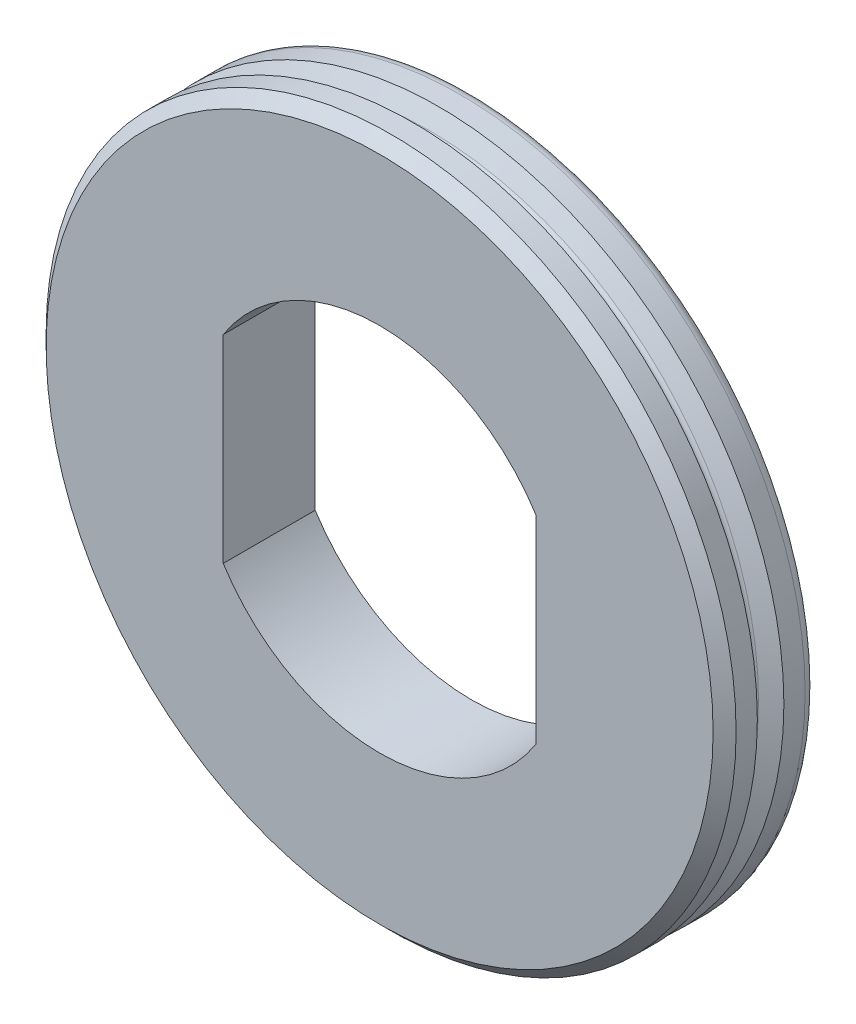
SolidWorks part; units mm, degrees
material "AISI 304"
ref_plane "Спереди" through (0, 0, 0) normal (0, 0, 1) x (1, 0, 0)
ref_plane "Сверху" through (0, 0, 0) normal (0, 1, 0) x (1, 0, 0)
ref_plane "Справа" through (0, 0, 0) normal (1, 0, 0) x (0, 0, -1)
sketch "Эскиз1" plane through (0, 0, 0) normal (0, 0, 1) x (1, 0, 0)
  line L2 (6.8, 4.3084) -> (6.8, -4.3084)
  line L4 (-6.8, 4.3084) -> (-6.8, -4.3084)
  circle A0 centre (0, 0) radius 15
  arc A1 (-6.8, -4.3084) -> (6.8, -4.3084) centre (0, 0) ccw
  arc A2 (6.8, 4.3084) -> (-6.8, 4.3084) centre (0, 0) ccw
  point P6 (6.8, 0)
  point P8 (-6.8, 0)
  point P9 (0, -8.05)
  point P11 (0, 8.05)
  dimension "D1" = 8.05
  dimension "D2" = 30
  dimension "D3" = 13.6
extrude "Бобышка-Вытянуть2" add sketch "Эскиз1" along normal mid plane 4
sketch "Эскиз2" plane through (0, 0, 0) normal (1, 0, 0) x (0, 0, -1)
  line L0 (-2, 15) -> (-2, -15) construction
  line L1 (-2, 15) -> (-2, -15) construction
  line L2 (-0.5774, 15) -> (0.5774, 15)
  line L3 (0.5774, 15) -> (0, 14)
  line L4 (0, 14) -> (-0.5774, 15)
  line L5 (-3.2487, 0) -> (4.3764, 0) construction
  point P5 (0, 15)
  dimension "D1" = 1
  dimension "D2" = 60
revolve "Вырез-Повернуть1" cut sketch "Эскиз2" angle 360 about L5
fillet "Скругление1" radius 0.2 1 edges at (14, 0, 0)
chamfer "Фаска1" distance 0.5 angle 45 1 edges at (15, 0, 2)
fillet "Скругление2" radius 0.5 1 edges at (15, 0, -2)
